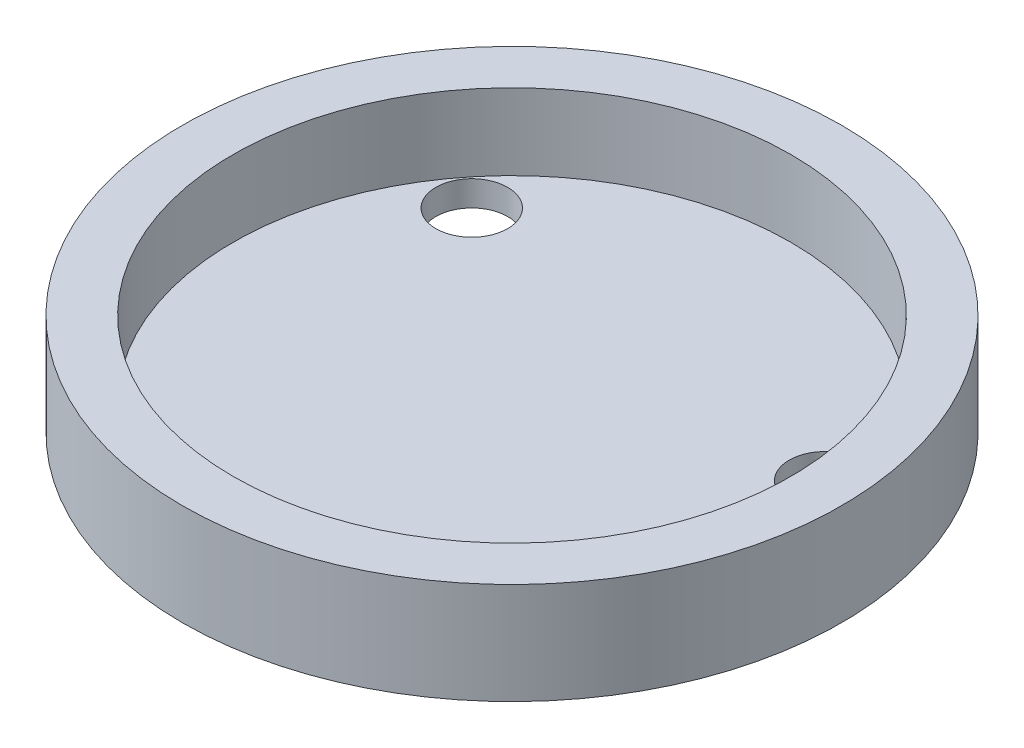
SolidWorks part; units mm, degrees
ref_plane "Front Plane" through (0, 0, 0) normal (0, 0, 1) x (1, 0, 0)
ref_plane "Top Plane" through (0, 0, 0) normal (0, 1, 0) x (1, 0, 0)
ref_plane "Right Plane" through (0, 0, 0) normal (1, 0, 0) x (0, 0, -1)
sketch "Sketch1" plane through (0, 0, 0) normal (0, 1, 0) x (1, 0, 0)
  circle A0 centre (0, 0) radius 65
  circle A1 centre (0, 0) radius 42 construction
  dimension "D1" = 130
  dimension "D2" = 84
extrude "Boss-Extrude1" add sketch "Sketch1" along normal blind 20
sketch "Sketch2" plane through (0, 20, 0) normal (0, 1, 0) x (1, 0, 0)
  circle A0 centre (0, 0) radius 55
  dimension "D1" = 110
extrude "Cut-Extrude1" cut sketch "Sketch2" against normal blind 15
sketch "Sketch3" plane through (0, 0, 0) normal (0, -1, 0) x (1, 0, 0)
  circle A0 centre (0, 0) radius 47.51 construction
  point P3 (26.4243, 39.4836)
  point P5 (0, -47.51)
  point P7 (-47.51, 0)
  dimension "D1" = 95.02
hole_wizard "Ø1.0mm Dowel Hole1" positions "Sketch5" profile "Sketch6" hole size "Ø1.0" standard "ISO"
sketch "Sketch5" plane through (0, 0, 0) normal (0, -1, 0) x (-1, 0, 0)
  line L0 (0, 0) -> (37.328, 29.3908)
  line L2 (0, 0) -> (-44.1172, 17.6316)
  line L4 (0, 0) -> (6.7892, -47.0224)
  circle A0 centre (0, 0) radius 47.51 construction
  point P0 (37.328, 29.3908)
  point P4 (6.7892, -47.0224)
  point P6 (-44.1172, 17.6316)
  dimension "D1" = 120
  dimension "D2" = 120
sketch "Sketch6" plane through (-37.328, 0, -29.3908) normal (1, 0, 0) x (0, 0, -1)
  line L0 (0, 0) -> (0, 12.4)
  line L1 (0, 12.4) -> (7.075, 8.1489)
  line L2 (7.075, 8.1489) -> (7.075, 0)
  line L5 (7.075, 0) -> (0, 0)
  line L10 (0, 12.4) -> (-7.075, 8.1489) construction
  line L11 (0, -6.35) -> (0, 107.95) construction
  dimension "Hole Dia." = 14.15
  dimension "Hole Depth" = 12.4
  dimension "Drill Angle" = 118
